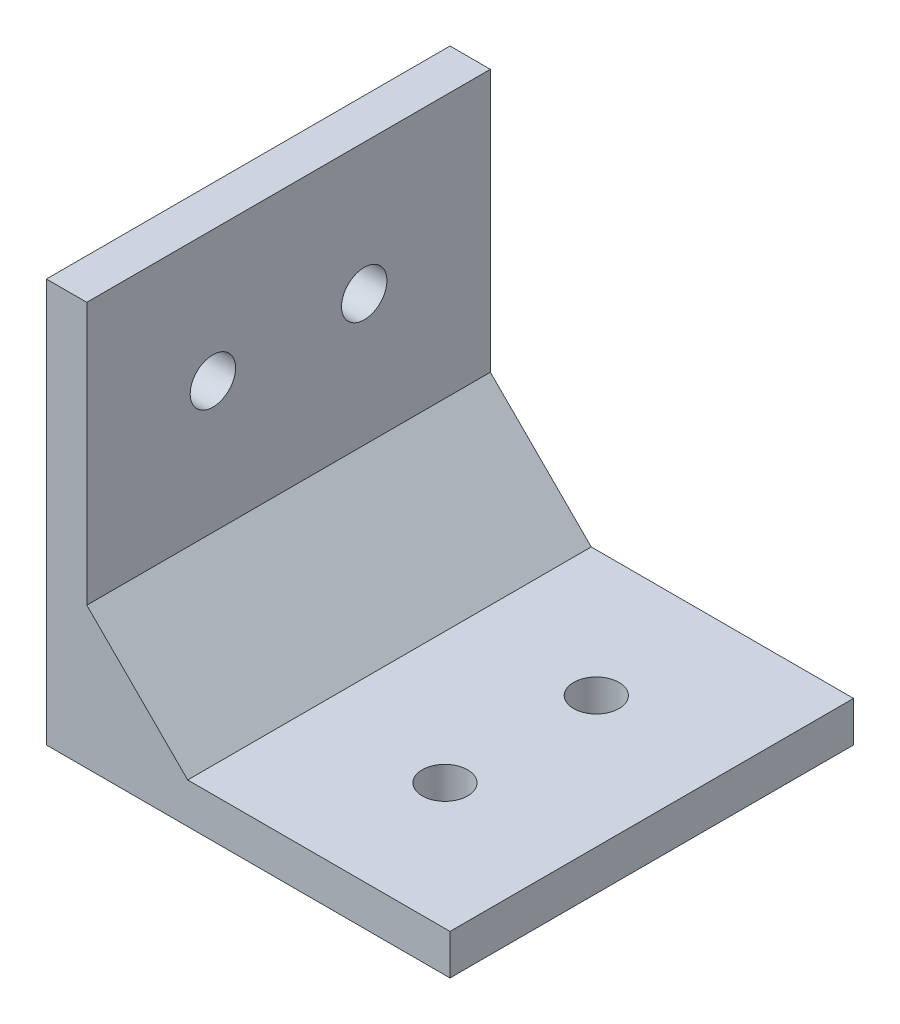
SolidWorks part; units mm, degrees
material "ABS"
ref_plane "Piano frontale" through (0, 0, 0) normal (0, 0, 1) x (1, 0, 0)
ref_plane "Piano superiore" through (0, 0, 0) normal (0, 1, 0) x (1, 0, 0)
ref_plane "Piano destro" through (0, 0, 0) normal (1, 0, 0) x (0, 0, -1)
sketch "Schizzo1" plane through (0, 0, 0) normal (0, 1, 0) x (1, 0, 0)
  line L1 (0, 0) -> (-40, 0)
  line L2 (0, 0) -> (0, 40)
  line L3 (0, 40) -> (-40, 40)
  line L4 (-40, 0) -> (-40, 40)
  dimension "D1" = 40
extrude "Estrusione-Estrusione1" add sketch "Schizzo1" along normal blind 4
sketch "Schizzo2" plane through (0, 4, 0) normal (0, 1, 0) x (1, 0, 0)
  line L0 (-36, 0) -> (-40, 0)
  line L1 (-40, 0) -> (0, 0) construction
  line L2 (-40, 0) -> (-40, 40)
  line L7 (-36, 40) -> (-36, 0)
  line L8 (0, 40) -> (-40, 40) construction
  line L9 (-40, 40) -> (-36, 40)
  dimension "D1" = 4
extrude "Estrusione-Estrusione2" add sketch "Schizzo2" along normal blind 36
chamfer "Smusso1" distance 10 angle 45 1 edges at (-36, 4, -20)
hole_wizard "Foro per Vite M4-1" positions "Schizzo3" profile "Schizzo4" hole size "M4" standard "DIN"
sketch "Schizzo3" plane through (0, 0, 0) normal (0, -1, 0) x (-1, 0, 0)
  line L0 (13, 12.5) -> (13, 27.5) construction
  line L2 (0, 0) -> (0, 40) construction
  line L3 (0, 20) -> (13, 20) construction
  point P29 (13, 27.5)
  point P31 (13, 12.5)
  point P41 (13, 18.2112)
  dimension "D1" = 15
  dimension "D2" = 13
sketch "Schizzo4" plane through (-13, 0, -27.5) normal (1, 0, 0) x (0, 0, -1)
  line L0 (0, 0) -> (0, 10.3519)
  line L1 (0, 10.3519) -> (2.25, 9)
  line L2 (2.25, 9) -> (2.25, 0)
  line L5 (2.25, 0) -> (0, 0)
  line L10 (0, 10.3519) -> (-2.25, 9) construction
  line L11 (0, -6.35) -> (0, 107.95) construction
  dimension "Hole Dia." = 4.5
  dimension "Hole Depth" = 9
  dimension "Drill Angle" = 118
hole_wizard "Foro per Vite M4-3" positions "Schizzo7" profile "Schizzo8" hole size "M4" standard "DIN"
sketch "Schizzo7" plane through (-40, 0, 0) normal (-1, 0, 0) x (0, 0, 1)
  line L0 (-27.5, 27) -> (-12.5, 27) construction
  line L2 (-20, 27) -> (-20, 40) construction
  line L3 (-40, 40) -> (0, 40) construction
  point P28 (-27.5, 27)
  point P30 (-12.5, 27)
  dimension "D1" = 13
  dimension "D2" = 15
sketch "Schizzo8" plane through (-40, 27, -27.5) normal (0, 1, 0) x (0, 0, 1)
  line L0 (0, 0) -> (0, 10.3519)
  line L1 (0, 10.3519) -> (2.25, 9)
  line L2 (2.25, 9) -> (2.25, 0)
  line L5 (2.25, 0) -> (0, 0)
  line L10 (0, 10.3519) -> (-2.25, 9) construction
  line L11 (0, -6.35) -> (0, 107.95) construction
  dimension "Hole Dia." = 4.5
  dimension "Hole Depth" = 9
  dimension "Drill Angle" = 118
